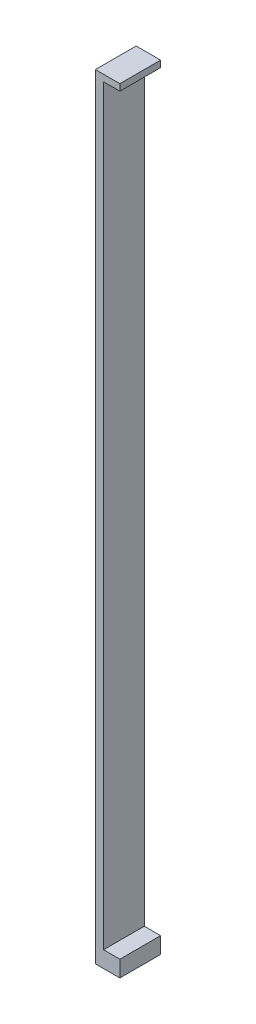
SolidWorks part; units mm, degrees
ref_plane "Front Plane" through (0, 0, 0) normal (1, 0, 0) x (0, 1, 0)
ref_plane "Top Plane" through (0, 0, 0) normal (0, 0, 1) x (0, 1, 0)
ref_plane "Right Plane" through (0, 0, 0) normal (0, 1, 0) x (-1, 0, 0)
sketch "Sketch1" plane through (0, 0, 0) normal (1, 0, 0) x (0, 1, 0)
  line L1 (0, 0) -> (95, 0)
  line L2 (0, 0) -> (0, 5)
  line L3 (0, 5) -> (95, 5)
  line L4 (95, 0) -> (95, 5)
  dimension "D1" = 95
  dimension "D2" = 5
extrude "Boss-Extrude1" add sketch "Sketch1" along normal blind 3
sketch "Sketch2" plane through (3, 0, 0) normal (1, 0, 0) x (0, 1, 0)
  line L0 (95, 5) -> (0, 5) construction
  line L1 (2, 5) -> (94.2, 5)
  line L2 (2, 5) -> (2, 0)
  line L3 (2, 0) -> (94.2, 0)
  line L4 (94.2, 5) -> (94.2, 0)
  line L5 (0, 0) -> (95, 0) construction
  line L6 (0, 5) -> (0, 0) construction
  dimension "D1" = 2
  dimension "D2" = 92.2
extrude "Cut-Extrude1" cut sketch "Sketch2" against normal blind 2
